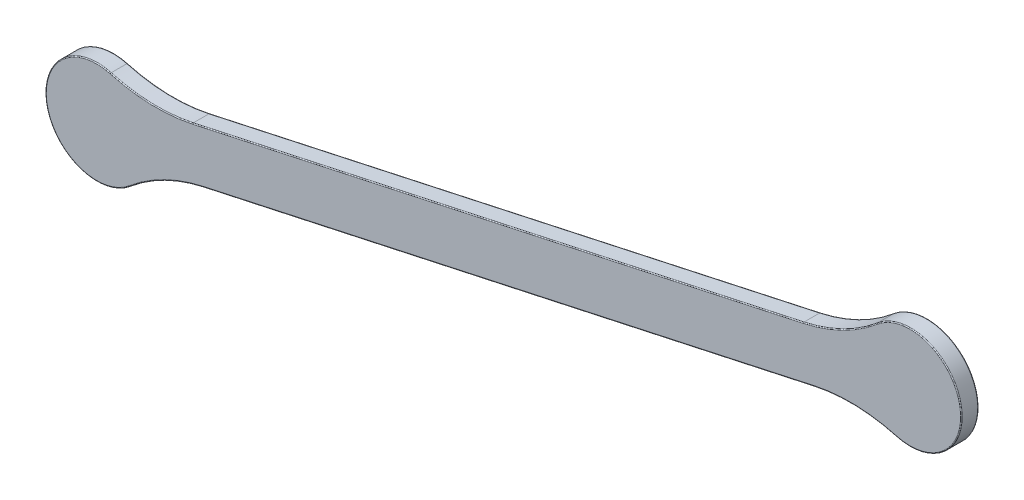
SolidWorks part; units mm, degrees
ref_plane "前视基准面" through (0, 0, 0) normal (0, 0, 1) x (1, 0, 0)
ref_plane "上视基准面" through (0, 0, 0) normal (0, 1, 0) x (1, 0, 0)
ref_plane "右视基准面" through (0, 0, 0) normal (1, 0, 0) x (0, 0, -1)
sketch "草图1" plane through (0, 0, 0) normal (0, 0, 1) x (1, 0, 0)
  line L0 (-101.4725, 222.2302) -> (-244.1364, 191.1979) construction
  line L1 (-101.4725, 222.2302) -> (-244.1364, 191.1979) construction
  line L2 (-101.4725, 222.2302) -> (-244.1364, 191.1979) construction
  line L3 (-100.516, 217.833) -> (-243.1799, 186.8007)
  line L4 (-102.429, 226.6274) -> (-245.0929, 195.5951)
  arc A0 (-100.516, 217.833) -> (-102.429, 226.6274) centre (-101.4725, 222.2302) ccw
  arc A1 (-245.0929, 195.5951) -> (-243.1799, 186.8007) centre (-244.1364, 191.1979) ccw
  circle A2 centre (-244.1364, 191.1979) radius 9
  circle A3 centre (-101.4725, 222.2302) radius 9
  arc A4 (-101.4725, 217.7302) -> (-102.429, 226.6274) centre (-101.4725, 222.2302) cw
  arc A5 (-244.1364, 195.6979) -> (-243.1799, 186.8007) centre (-244.1364, 191.1979) cw
  point P0 (-101.4725, 222.2302)
  point P2 (-244.1364, 191.1979)
  point P7 (-172.8044, 206.714)
  dimension "D2" = 18
  dimension "D1" = 9
extrude "凸台-拉伸1" add sketch "草图1" against normal blind 3 contours L3 A3 L4 A0 | L3 A4 L4 A3 | A3 L4 A2 L3 | L4 A5 L3 A2 | L4 A2 L3 A1
fillet "圆角1" radius 30 4 edges at (-237.4767, 197.2517, -1.5) (-235.5638, 188.4574, -1.5) (-108.1321, 216.1764, -1.5) (-110.0451, 224.9707, -1.5)
fillet "圆角2" radius 0.15 16 edges at (-232.2634, 188.2765, 0) (-252.9308, 189.2849, 0) (-234.5497, 198.7872, 0) (-173.7609, 211.1112, 0) (-113.3455, 225.1516, 0) (-92.6781, 224.1432, 0) (-111.0592, 214.6409, 0) (-171.848, 202.3169, 0) (-113.3455, 225.1516, -3) (-173.7609, 211.1112, -3) (-234.5497, 198.7872, -3) (-252.9308, 189.2849, -3) (-232.2634, 188.2765, -3) (-171.848, 202.3169, -3) (-111.0592, 214.6409, -3) (-92.6781, 224.1432, -3)
